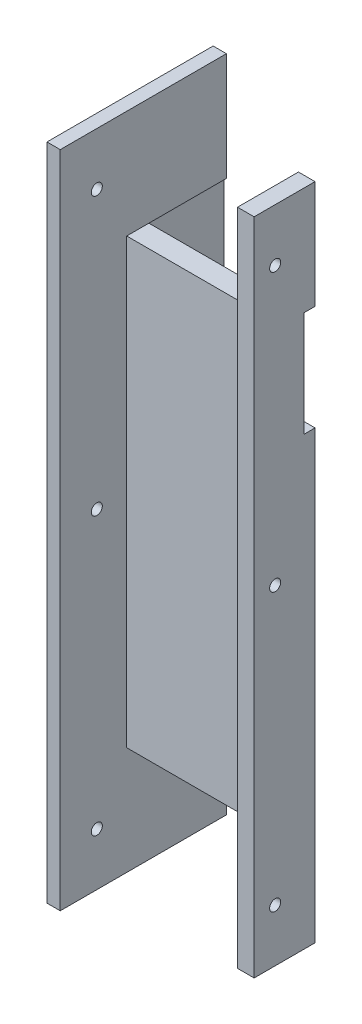
SolidWorks part; units mm, degrees
ref_plane "前视基准面" through (0, 0, 0) normal (0, 0, 1) x (1, 0, 0)
ref_plane "上视基准面" through (0, 0, 0) normal (0, 1, 0) x (1, 0, 0)
ref_plane "右视基准面" through (0, 0, 0) normal (1, 0, 0) x (0, 0, -1)
other "Configuration Table"
sketch "草图1" plane through (0, 0, 0) normal (1, 0, 0) x (0, 0, -1)
  line L0 (0, 31.9197) -> (0, -34.0629) construction
  line L1 (-4, -29.75) -> (1.5, -29.75)
  line L2 (-4, -29.75) -> (-4, 29.75)
  line L3 (-4, 29.75) -> (1.5, 29.75)
  line L4 (1.5, -29.75) -> (1.5, 29.75)
  line L5 (-4, -29.75) -> (1.5, 29.75) construction
  line L6 (-4, 29.75) -> (1.5, -29.75) construction
  line L7 (18.5819, 0) -> (-18.5363, 0) construction
  point P0 (-1.25, 0)
  dimension "D1" = 59.5
  dimension "D2" = 5.5
  dimension "D3" = 1.25
extrude "凸台-拉伸1" add sketch "草图1" along normal blind 1.5
sketch "草图2" plane through (0, 0, 0) normal (-1, 0, 0) x (0, 0, 1)
  line L2 (-1.5, -20) -> (1.5, -20)
  line L3 (-1.5, -20) -> (-1.5, 20)
  line L4 (-1.5, 20) -> (1.5, 20)
  line L5 (1.5, -20) -> (1.5, 20)
  line L6 (-1.5, -20) -> (1.5, 20) construction
  line L7 (-1.5, 20) -> (1.5, -20) construction
  point P1 (0, 0)
  dimension "D1" = 40
extrude "凸台-拉伸2" add sketch "草图2" along normal blind 12.5
sketch "草图3" plane through (-12.5, 0, 0) normal (-1, 0, 0) x (0, 0, 1)
  line L1 (-7.5, -29.75) -> (7.5, -29.75)
  line L2 (-7.5, -29.75) -> (-7.5, 29.75)
  line L3 (-7.5, 29.75) -> (7.5, 29.75)
  line L4 (7.5, -29.75) -> (7.5, 29.75)
  line L5 (-7.5, -29.75) -> (7.5, 29.75) construction
  line L6 (-7.5, 29.75) -> (7.5, -29.75) construction
  point P0 (0, 0)
  dimension "D1" = 15
  dimension "D2" = 59.5
extrude "凸台-拉伸3" add sketch "草图3" along normal blind 1.2
sketch "草图4" plane through (0, 0, -1.5) normal (0, 0, -1) x (-1, 0, 0)
  line L0 (-1.5, -29.75) -> (-1.5, 29.75) construction
  line L1 (12.5, 20) -> (-1.5, 20)
  line L2 (12.5, 20) -> (12.5, 10.5)
  line L3 (12.5, 10.5) -> (-1.5, 10.5)
  line L4 (-1.5, 20) -> (-1.5, 10.5)
  dimension "D1" = 9.5
extrude "切除-拉伸1" cut sketch "草图4" against normal blind 1
sketch "草图5" plane through (-12.5, 0, 0) normal (1, 0, 0) x (0, 0, -1)
  line L0 (7.5, 29.75) -> (7.5, -29.75) construction
  line L1 (0.5, 10.5) -> (7.5, 10.5)
  line L2 (0.5, 10.5) -> (0.5, 20)
  line L3 (0.5, 20) -> (7.5, 20)
  line L4 (7.5, 10.5) -> (7.5, 20)
  line L5 (-1.5, 20) -> (0.5, 20) construction
extrude "切除-拉伸2" cut sketch "草图5" against normal blind 0.2
sketch "草图6" plane through (-12.5, 0, 0) normal (1, 0, 0) x (0, 0, -1)
  line L0 (7.5, -29.75) -> (-7.5, -29.75) construction
  line L1 (-7.5, -29.75) -> (-7.5, 29.75) construction
  line L2 (7.5, 10.5) -> (7.5, -29.75) construction
  line L3 (-4.2, -25) -> (-4.2, 0) construction
  line L4 (3.8, -16.5) -> (3.8, 7.5) construction
  circle A0 centre (-4.2, -25) radius 0.5
  circle A1 centre (3.8, -16.5) radius 0.5
  circle A2 centre (-4.2, 0) radius 0.5
  circle A3 centre (-4.2, 25) radius 0.5
  circle A4 centre (3.8, 7.5) radius 0.5
  dimension "D1" = 1
  dimension "D2" = 4.75
  dimension "D3" = 3.3
  dimension "D4" = 13.25
  dimension "D5" = 3.7
  dimension "D7" = 25
  dimension "D9" = 24
  dimension "D6" = 3
  dimension "D8" = 2
extrude "切除-拉伸3" cut sketch "草图6" against normal blind 2.2
sketch "草图7" plane through (1.5, 0, 0) normal (1, 0, 0) x (0, 0, -1)
  line L0 (-2.1, 33.1033) -> (-2.1, -35.3509) construction
  line L3 (-4, -29.75) -> (1.5, -29.75) construction
  line L4 (-2.1, -25) -> (-2.1, 0) construction
  line L5 (1.5, -29.75) -> (1.5, 10.5) construction
  circle A0 centre (-2.1, -25) radius 0.5
  circle A1 centre (-2.1, 0) radius 0.5
  circle A2 centre (-2.1, 25) radius 0.5
  dimension "D1" = 1
  dimension "D2" = 4.75
  dimension "D4" = 25
  dimension "D5" = 3.6
  dimension "D3" = 3
extrude "切除-拉伸4" cut sketch "草图7" against normal blind 4
